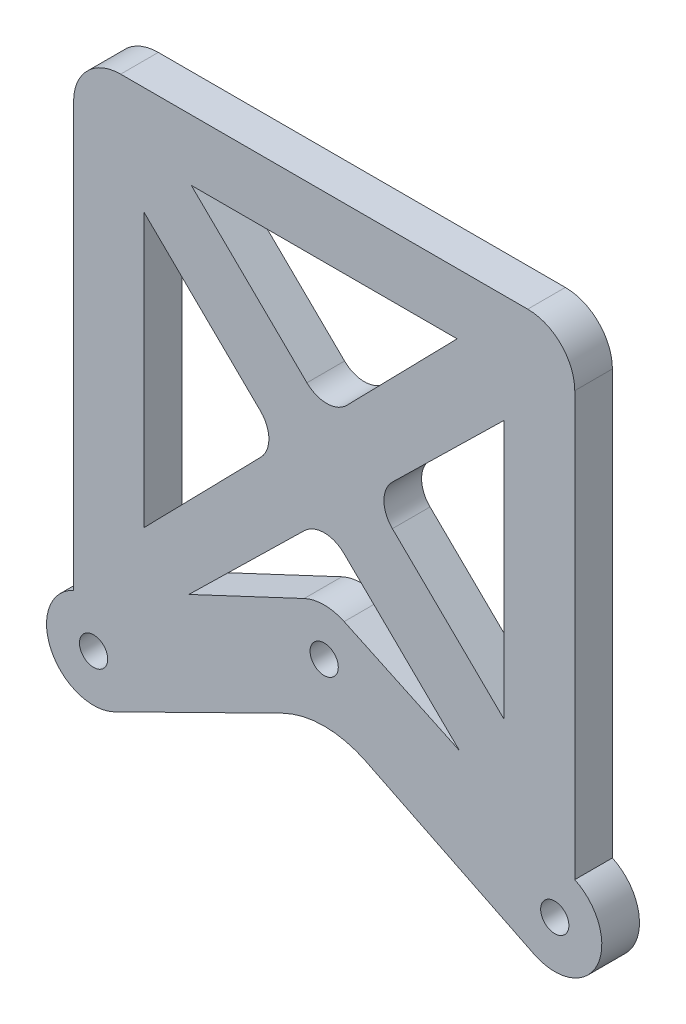
SolidWorks part; units mm, degrees
ref_plane "Front Plane" through (0, 0, 0) normal (0, 0, 1) x (1, 0, 0)
ref_plane "Top Plane" through (0, 0, 0) normal (0, 1, 0) x (1, 0, 0)
ref_plane "Right Plane" through (0, 0, 0) normal (1, 0, 0) x (0, 0, -1)
sketch "Sketch1" plane through (0, 0, 0) normal (0, 0, 1) x (1, 0, 0)
  line L1 (-26.6245, -6.9738) -> (-22.3755, -16.0262) construction
  line L2 (-22.3755, -16.0262) -> (-4.4203, -7.1782)
  line L3 (0, 0) -> (-2.1245, 4.5262) construction
  line L4 (0, 0) -> (2.1245, 4.5262) construction
  line L5 (2.1245, 4.5262) -> (14.3745, -1.2238)
  line L6 (26.6245, -6.9738) -> (22.3755, -16.0262) construction
  line L7 (22.3755, -16.0262) -> (4.4203, -7.1782)
  line L8 (-26.6245, -6.9738) -> (-26.6245, 38.0262)
  line L9 (26.6245, -6.9738) -> (26.6245, 38.0262)
  line L10 (-19.1245, 2.5582) -> (-19.1245, 31.5466)
  line L11 (19.1245, 4.0207) -> (19.1245, 31.5466)
  line L12 (-21.6245, 43.0262) -> (21.6245, 43.0262)
  line L13 (-14.1245, 36.5466) -> (14.1245, 36.5466)
  line L14 (-19.1245, 31.5466) -> (-6.7784, 19.469)
  line L15 (-14.1245, 36.5466) -> (-1.8339, 24.5233)
  line L16 (14.1245, 36.5466) -> (2.4084, 24.57)
  line L17 (-14.3745, -1.2238) -> (-2.0979, 10.7858)
  line L18 (2.0979, 10.7858) -> (14.3745, -1.2238)
  line L19 (-6.7317, 15.2266) -> (-19.1245, 2.5582)
  line L20 (7.2478, 19.9282) -> (19.1245, 31.5466)
  line L21 (7.2478, 15.6392) -> (19.1245, 4.0207)
  line L22 (-14.3745, -1.2238) -> (-2.1245, 4.5262)
  arc A3 (-26.6245, -6.9738) -> (-22.2051, -15.9422) centre (-24.5, -11.5) ccw
  arc A4 (2.1245, 4.5262) -> (-2.1245, 4.5262) centre (0, 0) ccw
  arc A5 (22.2051, -15.9422) -> (26.6245, -6.9738) centre (24.5, -11.5) ccw
  arc A6 (-4.4203, -7.1782) -> (4.4203, -7.1782) centre (0, -16.1482) cw
  arc A7 (26.6245, 38.0262) -> (21.6245, 43.0262) centre (21.6245, 38.0262) ccw
  arc A8 (2.0979, 10.7858) -> (-2.0979, 10.7858) centre (0, 8.6413) ccw
  arc A9 (7.2478, 19.9282) -> (7.2478, 15.6392) centre (9.3457, 17.7837) ccw
  arc A10 (-26.6245, 38.0262) -> (-21.6245, 43.0262) centre (-21.6245, 38.0262) cw
  arc A11 (-6.7784, 19.469) -> (-6.7317, 15.2266) centre (-8.8762, 17.3245) cw
  arc A12 (2.4084, 24.57) -> (-1.8339, 24.5233) centre (0.2639, 26.6679) cw
  point P27 (-19.1245, 36.5466)
  point P30 (-26.6245, 43.0262)
  point P39 (5.0556, 17.7837)
  point P42 (-4.6339, 17.3711)
  circle B0 centre (-24.5, -11.5) radius 1.5
  circle B1 centre (0, 0) radius 1.5
  circle B2 centre (24.5, -11.5) radius 1.5
  dimension "D1" = 10
  dimension "D2" = 10
  dimension "D3" = 10
  dimension "D4" = 10
  dimension "D9" = 5
  dimension "D8" = 3
  dimension "D5" = 50
  dimension "D6" = 7.5
  dimension "D7" = 7.5
sketch_block_instance "Block1-1"
sketch_block "Block1"
extrude "Boss-Extrude1" add sketch "Sketch1" along normal blind 4 contours A10 L8 A3 L2 A6 L7 A5 L9 A7 L12 B2 B1 B0 A9 L20 L11 L21 A8 L18 L5 A4 L22 L17 L14 A11 L19 L10 L16 A12 L15 L13
